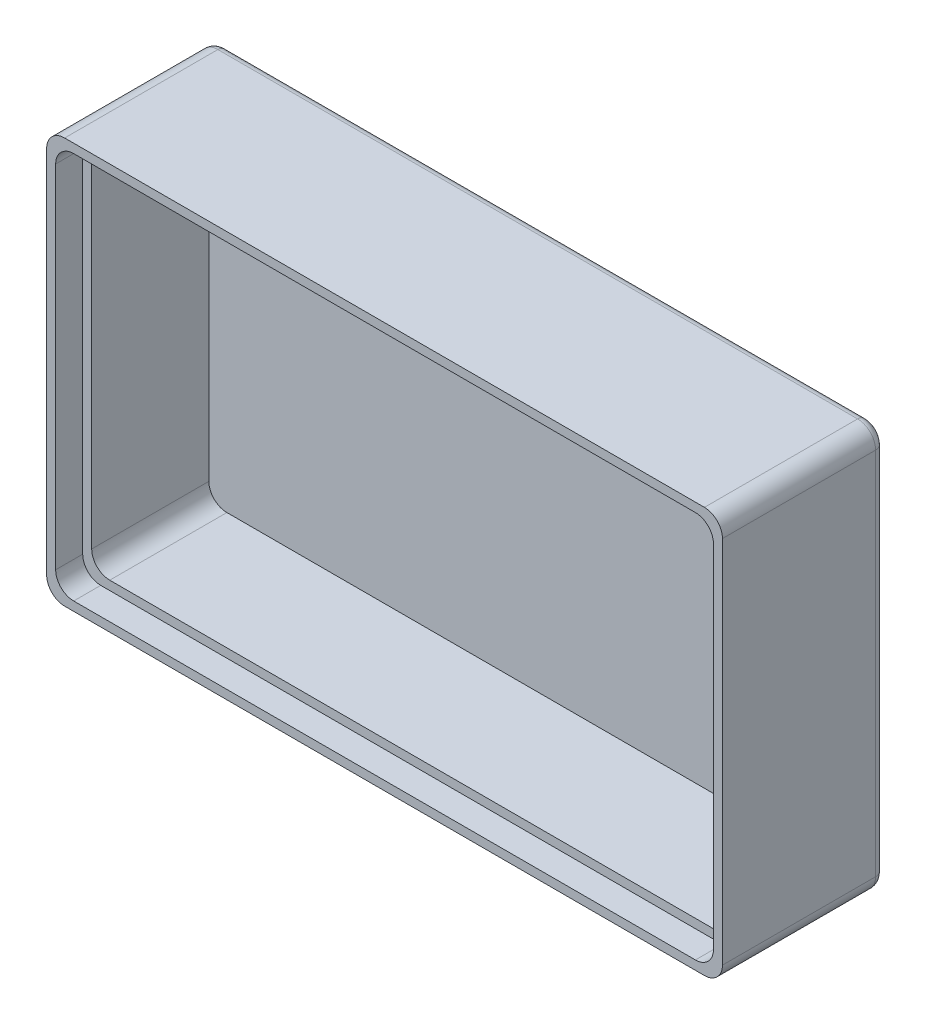
SolidWorks part; units mm, degrees
ref_plane "前视基准面" through (0, 0, 0) normal (0, 0, 1) x (1, 0, 0)
ref_plane "上视基准面" through (0, 0, 0) normal (0, 1, 0) x (1, 0, 0)
ref_plane "右视基准面" through (0, 0, 0) normal (1, 0, 0) x (0, 0, -1)
sketch "草图1" plane through (0, 0, 0) normal (0, 0, 1) x (1, 0, 0)
  line L1 (-37.5, 22.5) -> (37.5, 22.5)
  line L2 (-37.5, 22.5) -> (-37.5, -22.5)
  line L3 (-37.5, -22.5) -> (37.5, -22.5)
  line L4 (37.5, 22.5) -> (37.5, -22.5)
  dimension "D1" = 75
  dimension "D2" = 45
  dimension "D3" = 37.5
  dimension "D4" = 22.5
extrude "凸台-拉伸1" add sketch "草图1" along normal blind 18
sketch "草图2" plane through (0, 0, 18) normal (0, 0, 1) x (1, 0, 0)
  line L0 (-35.5, 20.5) -> (-35.5, -20.5)
  line L1 (-35.5, -20.5) -> (35.5, -20.5)
  line L2 (35.5, -20.5) -> (35.5, 20.5)
  line L3 (35.5, 20.5) -> (-35.5, 20.5)
extrude "切除-拉伸1" cut sketch "草图2" against normal blind 16
sketch "草图3" plane through (0, 0, 18) normal (0, 0, 1) x (1, 0, 0)
  line L0 (-35.5, -20.5) -> (35.5, -20.5) construction
  line L1 (35.5, -20.5) -> (35.5, 20.5) construction
  line L2 (35.5, 20.5) -> (-35.5, 20.5) construction
  line L3 (-35.5, 20.5) -> (-35.5, -20.5) construction
  line L4 (-35.5, -20.5) -> (35.5, -20.5)
  line L5 (35.5, -20.5) -> (35.5, 20.5)
  line L6 (35.5, 20.5) -> (-35.5, 20.5)
  line L7 (-35.5, 20.5) -> (-35.5, -20.5)
  line L8 (-36.5, -21.5) -> (36.5, -21.5)
  line L9 (36.5, -21.5) -> (36.5, 21.5)
  line L10 (36.5, 21.5) -> (-36.5, 21.5)
  line L11 (-36.5, 21.5) -> (-36.5, -21.5)
  dimension "D1" = 1
extrude "切除-拉伸2" cut sketch "草图3" against normal blind 3
fillet "圆角1" radius 2 12 edges at (-37.5, -22.5, 9) (37.5, -22.5, 9) (37.5, 22.5, 9) (-37.5, 22.5, 9) (-35.5, 20.5, 8.5) (35.5, 20.5, 8.5) (35.5, -20.5, 8.5) (-35.5, -20.5, 8.5) (-36.5, -21.5, 16.5) (36.5, -21.5, 16.5) (36.5, 21.5, 16.5) (-36.5, 21.5, 16.5)
fillet "圆角2" radius 1 8 edges at (36.9142, -21.9142, 0) (37.5, 0, 0) (36.9142, 21.9142, 0) (0, 22.5, 0) (-36.9142, 21.9142, 0) (-37.5, 0, 0) (-36.9142, -21.9142, 0) (0, -22.5, 0)
